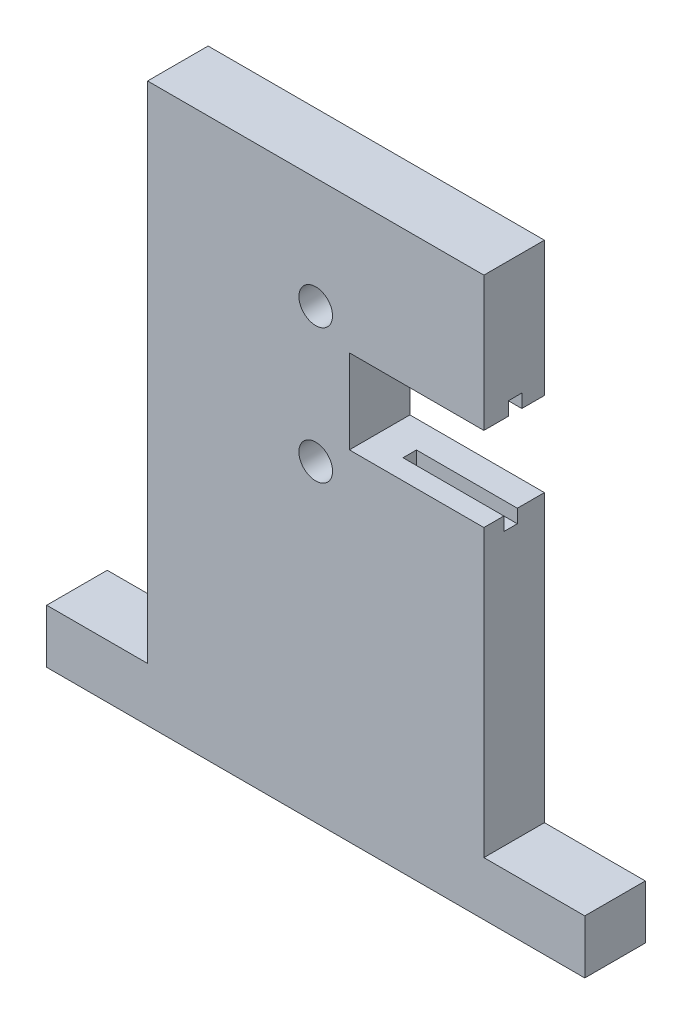
SolidWorks part; units mm, degrees
ref_plane "Plan de face" through (0, 0, 0) normal (0, 0, 1) x (1, 0, 0)
ref_plane "Plan de dessus" through (0, 0, 0) normal (0, 1, 0) x (1, 0, 0)
ref_plane "Plan de droite" through (0, 0, 0) normal (1, 0, 0) x (0, 0, -1)
sketch "Esquisse1" plane through (0, 0, 0) normal (0, 0, 1) x (1, 0, 0)
  line L0 (1.5532, 0) -> (81.5532, 0)
  line L1 (81.5532, 0) -> (81.5532, 8)
  line L2 (81.5532, 8) -> (66.5532, 8)
  line L3 (66.5532, 8) -> (66.5532, 83)
  line L4 (66.5532, 83) -> (16.5532, 83)
  line L5 (16.5532, 83) -> (16.5532, 8)
  line L6 (16.5532, 8) -> (1.5532, 8)
  line L7 (1.5532, 8) -> (1.5532, 0)
  circle A0 centre (41.5532, 46.5) radius 2.5
  circle A1 centre (41.5532, 66.5) radius 2.5
  dimension "D7" = 5
  dimension "D8" = 5
  dimension "D10" = 20
  dimension "D1" = 8
  dimension "D2" = 8
  dimension "D3" = 15
  dimension "D4" = 15
  dimension "D5" = 50
  dimension "D6" = 75
  dimension "D9" = 46.5
  dimension "D11" = 25
  dimension "D12" = 25
extrude "Boss.-Extru.1" add sketch "Esquisse1" against normal blind 9
sketch "Esquisse2" plane through (66.5532, 0, 0) normal (1, 0, 0) x (0, 0, -1)
  line L0 (9, 8) -> (9, 83) construction
  line L1 (9, 63) -> (0, 63)
  line L2 (9, 63) -> (9, 50.5)
  line L3 (9, 50.5) -> (0, 50.5)
  line L4 (0, 63) -> (0, 50.5)
  line L5 (0, 8) -> (0, 83) construction
  line L6 (9, 83) -> (0, 83) construction
  line L7 (2.9105, 63) -> (6.0166, 63)
  line L8 (6.0166, 63) -> (14.119, 51.935)
  line L9 (14.119, 51.935) -> (10.8322, 49.5283)
  line L10 (10.8322, 49.5283) -> (2.9105, 63)
  dimension "D1" = 20
  dimension "D2" = 32.5
extrude "Enlèv. mat.-Extru.2" cut sketch "Esquisse2" against normal blind 20 contours L1 L4 L3 L2
sketch "Esquisse4" plane through (0, 50.5, 0) normal (0, 1, 0) x (1, 0, 0)
  line L0 (66.5532, 2.9738) -> (51.5532, 2.9738)
  line L1 (51.5532, 2.9738) -> (51.5532, 4.9738)
  line L2 (66.5532, 9) -> (66.5532, 0) construction
  line L3 (51.5532, 4.9738) -> (66.5532, 4.9738)
  line L4 (66.5532, 4.9738) -> (66.5532, 2.9738)
  dimension "D1" = 2
  dimension "D2" = 15
ref_plane "Plan2" through (66.5532, 50.5, 0) normal (0, 0, 1) x (1, 0, 0)
extrude "Enlèv. mat.-Extru.4" cut sketch "Esquisse4" against normal blind 2 contours L4 L0 L1 L3
sketch "Esquisse6" plane through (0, 63, 0) normal (0, -1, 0) x (1, 0, 0)
  line L0 (66.5532, -3.6387) -> (66.5532, -5.6387)
  line L1 (66.5532, -9) -> (66.5532, 0) construction
  line L2 (66.5532, -5.6387) -> (51.5532, -5.6387)
  line L3 (51.5532, -5.6387) -> (51.5532, -3.6387)
  line L4 (51.5532, -3.6387) -> (66.5532, -3.6387)
  dimension "D1" = 15
  dimension "D2" = 2
extrude "Enlèv. mat.-Extru.5" cut sketch "Esquisse6" against normal blind 2 contours L0 L2 L3 L4
